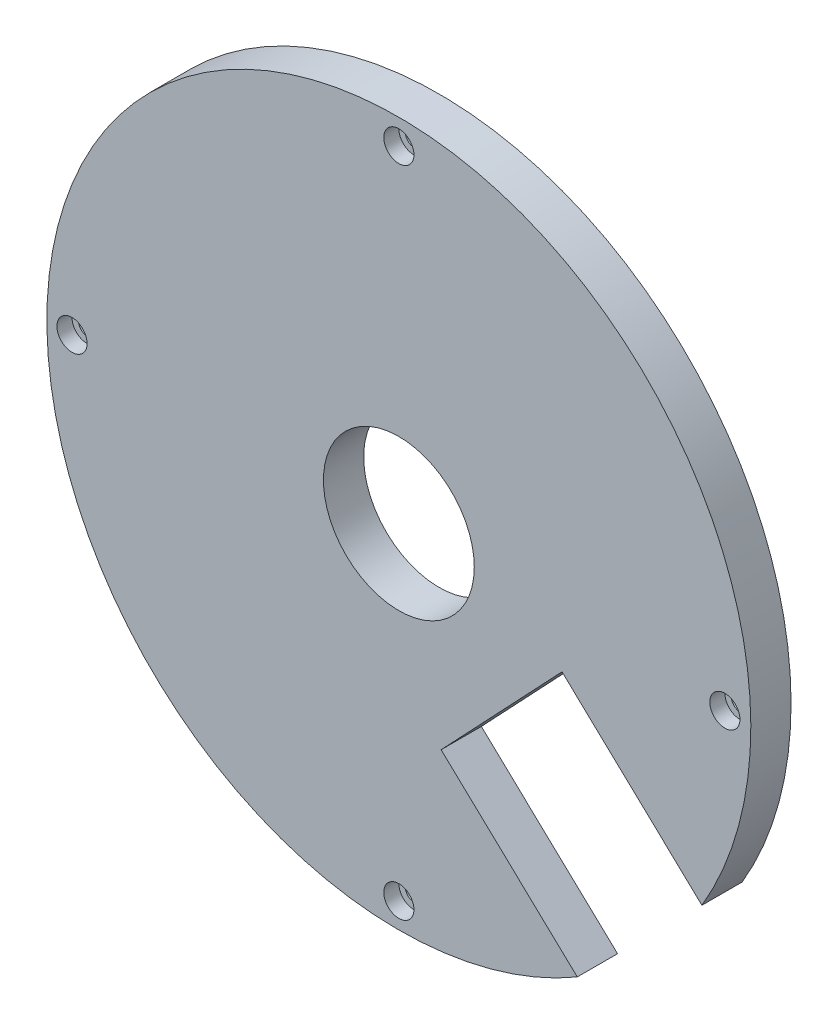
SolidWorks part; units mm, degrees
ref_plane "Ebene vorne" through (0, 0, 0) normal (1, 0, 0) x (0, 1, 0)
ref_plane "Ebene oben" through (0, 0, 0) normal (0, 0, 1) x (0, 1, 0)
ref_plane "Ebene rechts" through (0, 0, 0) normal (0, 1, 0) x (-1, 0, 0)
sketch "Skizze1" plane through (0, 0, 0) normal (0, 0, 1) x (0, 1, 0)
  circle A0 centre (0, 0) radius 70
  circle A1 centre (0, 0) radius 15
  dimension "D1" = 140
  dimension "D2" = 30
extrude "Aufsatz-Linear austragen1" add sketch "Skizze1" along normal blind 8
sketch "Skizze2" plane through (0, 0, 8) normal (0, 0, 1) x (1, 0, 0)
  line L0 (0, 0) -> (0, 32.8458) construction
  line L1 (-70, 0) -> (87.0508, 0) construction
  circle A1 centre (0, 0) radius 65 construction
  circle A2 centre (0, 65) radius 1.7
  circle A3 centre (64.8372, 0.1899) radius 1.7
  circle A4 centre (0, -65) radius 1.7
  circle A5 centre (-65, 0) radius 1.7
extrude "Schnitt-Linear austragen1" cut sketch "Skizze2" against normal blind 8
sketch "Skizze3" plane through (0, 0, 8) normal (0, 0, 1) x (1, 0, 0)
  circle A0 centre (0, 65) radius 3
  circle A2 centre (64.8372, 0.1899) radius 3
  circle A3 centre (0, -65) radius 3
  circle A4 centre (-65, 0) radius 3
extrude "Schnitt-Linear austragen2" cut sketch "Skizze3" against normal blind 3
sketch "Skizze4" plane through (0, 0, 8) normal (0, 0, 1) x (1, 0, 0)
  line L0 (0, 0) -> (49.4975, -49.4975) construction
  line L7 (66.5503, -89.6901) -> (8.4054, -34.7432)
  line L8 (66.5503, -89.6901) -> (90.5896, -64.2517)
  line L9 (8.4054, -34.7432) -> (32.4446, -9.3048)
  line L10 (90.5896, -64.2517) -> (32.4446, -9.3048)
  line L11 (66.5503, -89.6901) -> (32.4446, -9.3048) construction
  line L12 (8.4054, -34.7432) -> (90.5896, -64.2517) construction
  circle A0 centre (0, 0) radius 70 construction
  dimension "D1" = 80
  dimension "D2" = 35
extrude "Schnitt-Linear austragen3" cut sketch "Skizze4" against normal blind 8
